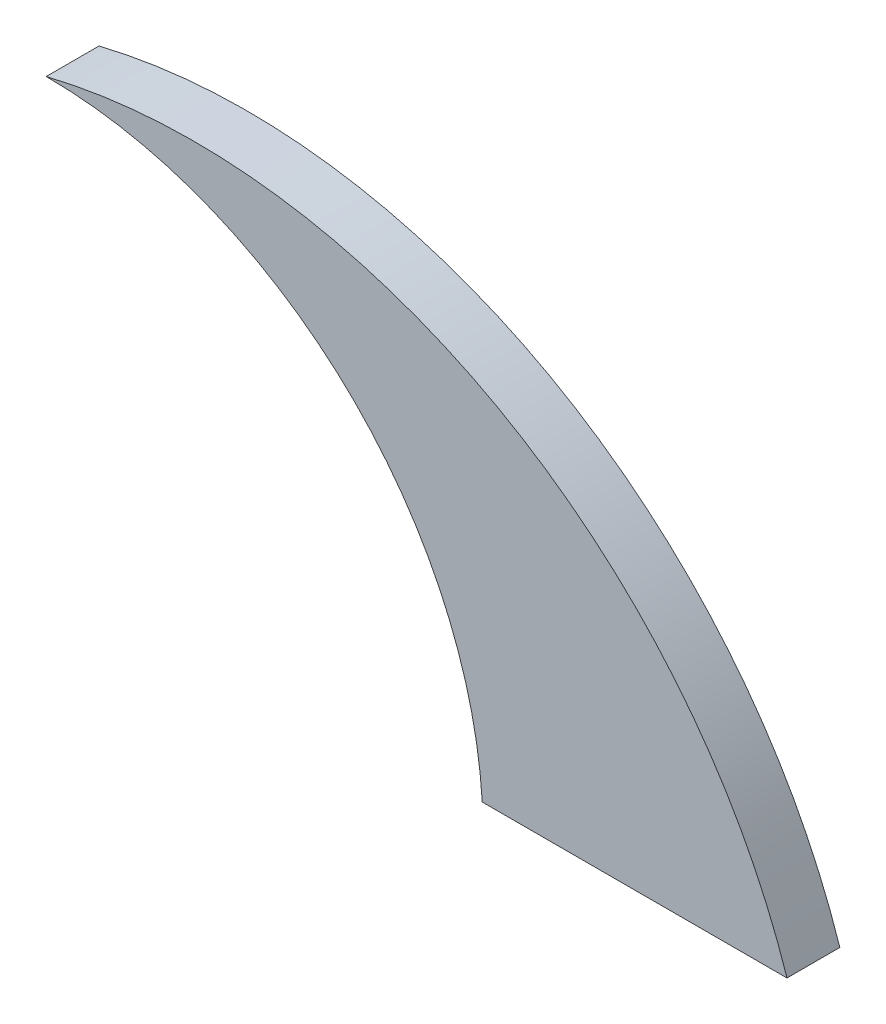
SolidWorks part; units mm, degrees
ref_plane "Front Plane" through (0, 0, 0) normal (0, 0, 1) x (1, 0, 0)
ref_plane "Top Plane" through (0, 0, 0) normal (0, 1, 0) x (1, 0, 0)
ref_plane "Right Plane" through (0, 0, 0) normal (1, 0, 0) x (0, 0, -1)
sketch "Sketch1" plane through (0, 0, 0) normal (0, 0, 1) x (1, 0, 0)
  line L0 (0, 0) -> (0, 180) construction
  line L1 (0, 0) -> (180, 0) construction
  line L2 (104.8048, 6.4) -> (178.0403, 6.4)
  circle A0 centre (0, 0) radius 105 construction
  circle A1 centre (0, 0) radius 180 construction
  arc A2 (0, 105) -> (104.8048, 6.4) centre (0, 0) cw
  circle A3 centre (35.6292, -40.7071) radius 150 construction
  arc A4 (0, 105) -> (178.0403, 6.4) centre (35.6292, -40.7071) cw
  dimension "D1" = 210
  dimension "D2" = 75
  dimension "D3" = 6.4
  dimension "D4" = 300
extrude "Boss-Extrude1" add sketch "Sketch1" along normal blind 12.7
